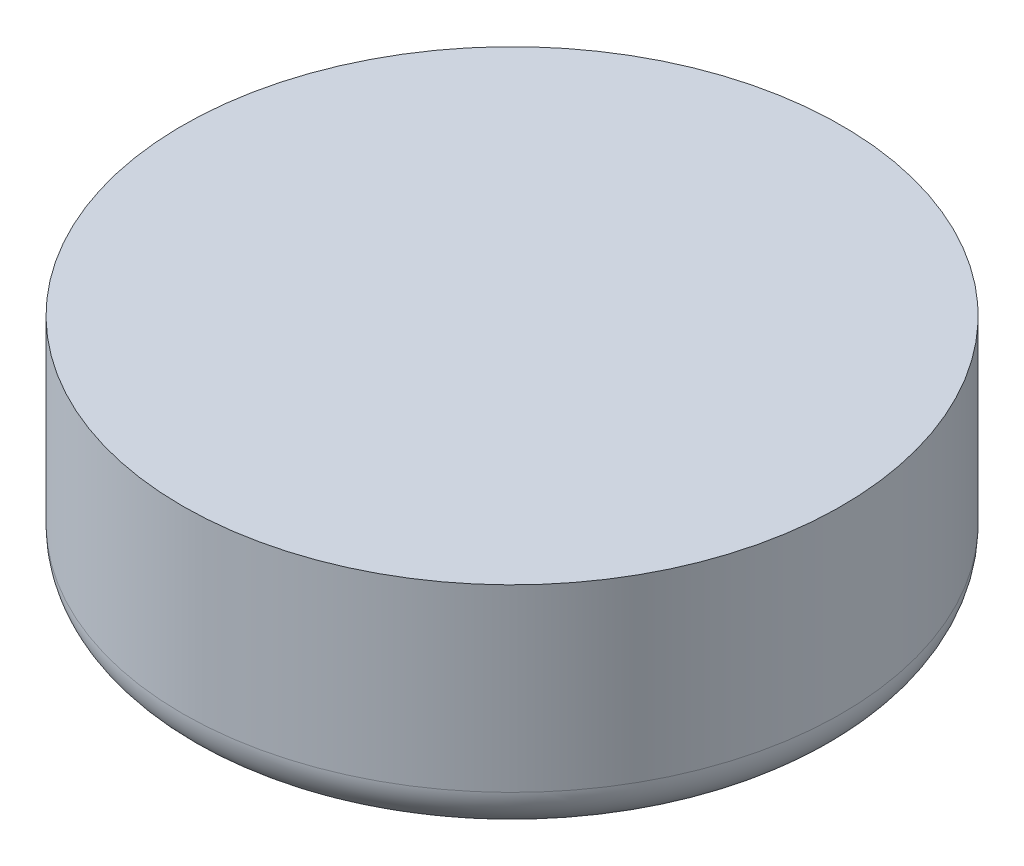
SolidWorks part; units mm, degrees
ref_plane "Front Plane" through (0, 0, 0) normal (0, 0, 1) x (1, 0, 0)
ref_plane "Top Plane" through (0, 0, 0) normal (0, 1, 0) x (1, 0, 0)
ref_plane "Right Plane" through (0, 0, 0) normal (1, 0, 0) x (0, 0, -1)
sketch "Sketch1" plane through (0, 0, 0) normal (0, 1, 0) x (1, 0, 0)
  circle A0 centre (0, 0) radius 22
  dimension "D1" = 44
extrude "Boss-Extrude1" add sketch "Sketch1" along normal blind 15
fillet "Fillet1" radius 3 1 edges at (0, 0, 22)
